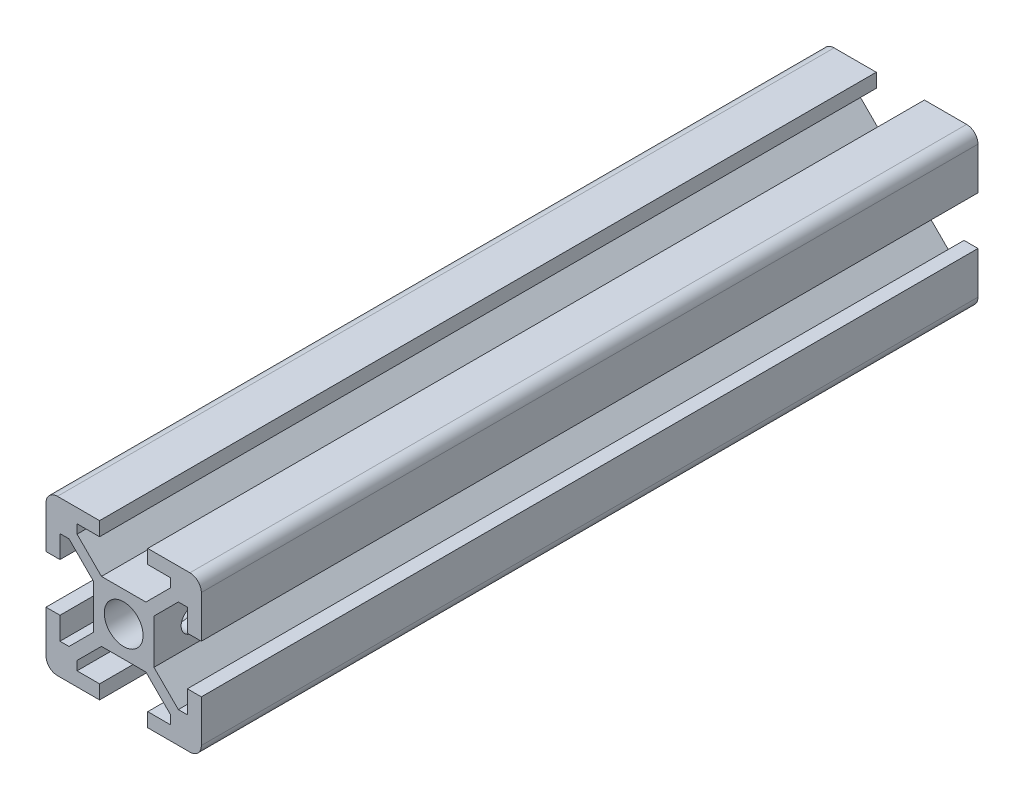
SolidWorks part; units mm, degrees
ref_plane "Front Plane" through (0, 0, 0) normal (0, 0, 1) x (1, 0, 0)
ref_plane "Top Plane" through (0, 0, 0) normal (0, 1, 0) x (1, 0, 0)
ref_plane "Right Plane" through (0, 0, 0) normal (1, 0, 0) x (0, 0, -1)
sketch "Sketch1" plane through (0, 0, 0) normal (0, 0, 1) x (1, 0, 0)
  line L0 (2.8606, 3.9) -> (6, 7.0394)
  line L5 (0, 3.9) -> (2.8606, 3.9)
  line L8 (3.9, 2.8606) -> (3.9, 0)
  line L9 (3.9, 0) -> (3.9, -2.8606)
  line L10 (3.9, -2.8606) -> (7.0394, -6)
  line L11 (6, 7.0394) -> (6, 8.2)
  line L12 (6, 8.2) -> (3.1, 8.2)
  line L13 (3.1, 8.2) -> (3.1, 10)
  line L14 (3.1, 10) -> (10, 10)
  line L15 (10, 10) -> (10, 3.1)
  line L16 (10, 3.1) -> (8.2, 3.1)
  line L17 (8.2, 3.1) -> (8.2, 6)
  line L18 (8.2, 6) -> (7.0394, 6)
  line L19 (7.0394, 6) -> (3.9, 2.8606)
  line L22 (7.0394, -6) -> (8.2, -6)
  line L23 (8.2, -6) -> (8.2, -3.1)
  line L24 (8.2, -3.1) -> (10, -3.1)
  line L25 (10, -3.1) -> (10, -10)
  line L26 (10, -10) -> (3.1, -10)
  line L27 (3.1, -10) -> (3.1, -8.2)
  line L28 (3.1, -8.2) -> (6, -8.2)
  line L29 (6, -8.2) -> (6, -7.0394)
  line L30 (6, -7.0394) -> (2.8606, -3.9)
  line L31 (2.8606, -3.9) -> (0, -3.9)
  line L32 (0, -3.9) -> (-2.8606, -3.9)
  line L33 (-2.8606, -3.9) -> (-6, -7.0394)
  line L34 (-6, -7.0394) -> (-6, -8.2)
  line L35 (-6, -8.2) -> (-3.1, -8.2)
  line L36 (-3.1, -8.2) -> (-3.1, -10)
  line L37 (-3.1, -10) -> (-10, -10)
  line L38 (-10, -10) -> (-10, -3.1)
  line L39 (-10, -3.1) -> (-8.2, -3.1)
  line L40 (-8.2, -3.1) -> (-8.2, -6)
  line L41 (-8.2, -6) -> (-7.0394, -6)
  line L42 (-7.0394, -6) -> (-3.9, -2.8606)
  line L43 (-3.9, -2.8606) -> (-3.9, 0)
  line L44 (-3.9, 0) -> (-3.9, 2.8606)
  line L45 (-3.9, 2.8606) -> (-7.0394, 6)
  line L46 (-7.0394, 6) -> (-8.2, 6)
  line L47 (-8.2, 6) -> (-8.2, 3.1)
  line L48 (-8.2, 3.1) -> (-10, 3.1)
  line L49 (-10, 3.1) -> (-10, 10)
  line L50 (-10, 10) -> (-3.1, 10)
  line L51 (-3.1, 10) -> (-3.1, 8.2)
  line L52 (-3.1, 8.2) -> (-6, 8.2)
  line L53 (-6, 8.2) -> (-6, 7.0394)
  line L54 (-6, 7.0394) -> (-2.8606, 3.9)
  line L55 (-2.8606, 3.9) -> (0, 3.9)
  circle A0 centre (0, 0) radius 2.5
  point P0 (0, 0)
  dimension "D9" = 5
  dimension "D1" = 45
  dimension "D2" = 10
  dimension "D3" = 6.1
  dimension "D4" = 3.1
  dimension "D5" = 1.47
  dimension "D6" = 4.3
  dimension "D7" = 6
  dimension "D8" = 4
extrude "Boss-Extrude1" add sketch "Sketch1" along normal blind 100
fillet "Fillet1" radius 1.47 4 edges at (-10, -10, 50) (-10, 10, 50) (10, -10, 50) (10, 10, 50)
sketch "Sketch2" plane through (-3.9, 0, 0) normal (-1, 0, 0) x (0, 0, 1)
  line L0 (100, 2.8606) -> (100, -2.8606) construction
  circle A0 centre (95, 0) radius 1.5
  circle A1 centre (85, 0) radius 1.5
  circle A2 centre (75, 0) radius 1.5
  circle A3 centre (65, 0) radius 1.5
  circle A4 centre (55, 0) radius 1.5
  circle A5 centre (45, 0) radius 1.5
  circle A6 centre (35, 0) radius 1.5
  circle A7 centre (25, 0) radius 1.5
  circle A8 centre (15, 0) radius 1.5
  circle A9 centre (5, 0) radius 1.5
  dimension "D1" = 3
  dimension "D2" = 5
  dimension "D3" = 10
extrude "Cut-Extrude1" cut sketch "Sketch2" against normal through all
